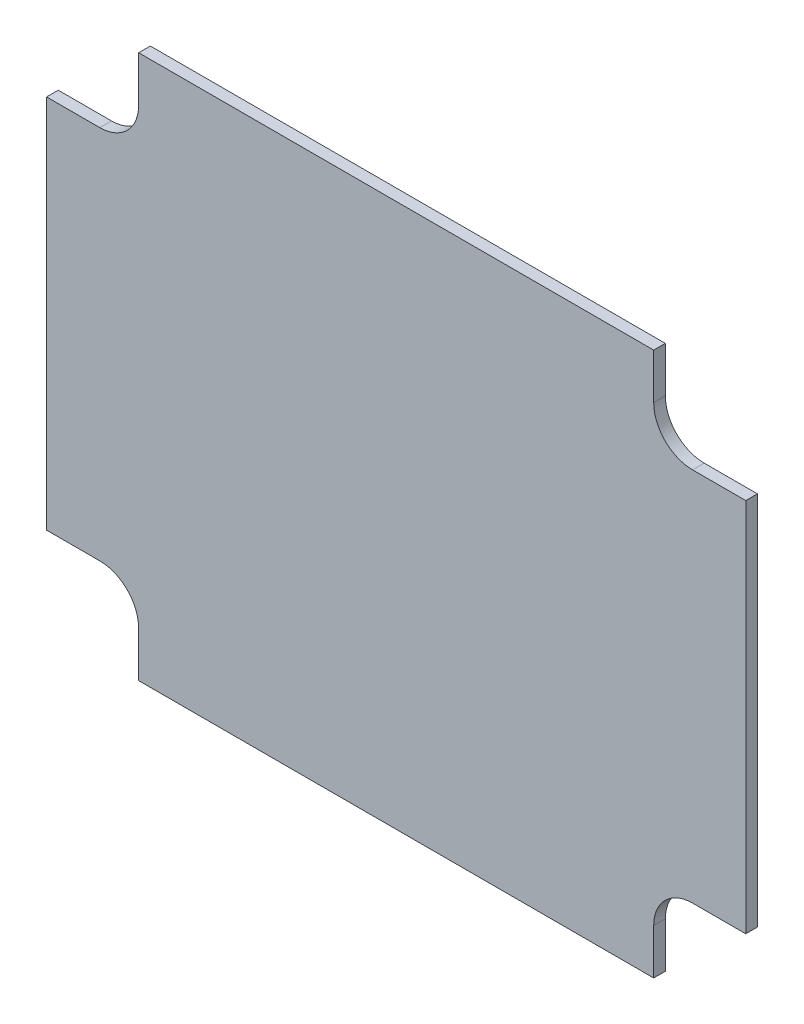
SolidWorks part; units mm, degrees
ref_plane "前视基准面" through (0, 0, 0) normal (0, 0, 1) x (1, 0, 0)
ref_plane "上视基准面" through (0, 0, 0) normal (0, 1, 0) x (1, 0, 0)
ref_plane "右视基准面" through (0, 0, 0) normal (1, 0, 0) x (0, 0, -1)
sketch "草图3" plane through (0, 0, 0) normal (0, 0, 1) x (1, 0, 0)
  line L0 (-0.0737, 34.1637) -> (-0.0737, -35.8363) construction
  line L1 (33.0763, 23.3137) -> (44.9263, 23.3137)
  line L2 (44.9263, -24.9863) -> (44.9263, 23.3137)
  line L3 (33.0763, -24.9863) -> (44.9263, -24.9863)
  line L4 (33.0763, -24.9863) -> (33.0763, 23.3137)
  line L5 (-45.0737, -0.8363) -> (44.9263, -0.8363) construction
  line L6 (-33.2237, -35.8363) -> (33.0763, -35.8363)
  line L7 (-33.2237, 23.3137) -> (33.0763, 23.3137)
  line L8 (-33.2237, 23.3137) -> (-33.2237, 34.1637)
  line L9 (-33.2237, 34.1637) -> (33.0763, 34.1637)
  line L10 (33.0763, 23.3137) -> (33.0763, 34.1637)
  line L11 (33.0763, -24.9863) -> (33.0763, -35.8363)
  line L12 (-33.2237, -24.9863) -> (33.0763, -24.9863)
  line L13 (-45.0737, 34.1637) -> (44.9263, 34.1637)
  line L14 (-45.0737, 34.1637) -> (-45.0737, -35.8363)
  line L15 (-45.0737, -35.8363) -> (44.9263, -35.8363)
  line L16 (44.9263, 34.1637) -> (44.9263, -35.8363)
  line L17 (-33.2237, -24.9863) -> (-45.0737, -24.9863)
  line L18 (-33.2237, -24.9863) -> (-33.2237, 23.3137)
  line L19 (-33.2237, 23.3137) -> (-45.0737, 23.3137)
  line L20 (-45.0737, -24.9863) -> (-45.0737, 23.3137)
  line L21 (-33.2237, -24.9863) -> (-45.0737, 23.3137) construction
  line L22 (-33.2237, 23.3137) -> (-45.0737, -24.9863) construction
  line L23 (-33.2237, -24.9863) -> (-33.2237, -35.8363)
  line L26 (-45.0737, -35.8363) -> (44.9263, -35.8363)
  line L32 (44.9263, 34.1637) -> (-45.0737, 34.1637)
  point P0 (-39.1487, -0.8363)
  dimension "D1" = 48.3
  dimension "D2" = 70
  dimension "D3" = 90
  dimension "D4" = 66.3
extrude "凸台-拉伸1" add sketch "草图3" along normal blind 1.5 contours L18 L12 L4 L7 | L18 L19 L14 L17 | L12 L23 L6 L11 | L7 L10 L9 L8 | L4 L3 L2 L1
fillet "圆角1" radius 5 4 edges at (-33.2237, -24.9863, 0.75) (33.0763, -24.9863, 0.75) (33.0763, 23.3137, 0.75) (-33.2237, 23.3137, 0.75)
